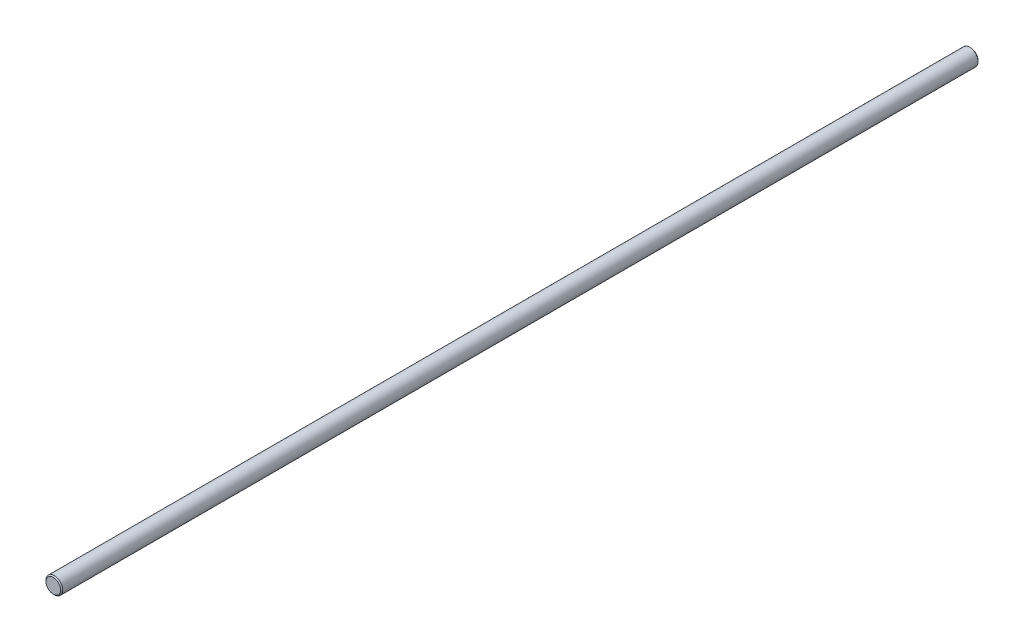
SolidWorks part; units mm, degrees
ref_plane "Front Plane" through (0, 0, 0) normal (0, 0, 1) x (1, 0, 0)
ref_plane "Top Plane" through (0, 0, 0) normal (0, 1, 0) x (1, 0, 0)
ref_plane "Right Plane" through (0, 0, 0) normal (1, 0, 0) x (0, 0, -1)
ref_plane "Plane1" through (0, 0, 0) normal (0, -1, 0) x (1, 0, 0)
sketch "Sketch1" plane through (0, 0, 0) normal (0, -1, 0) x (1, 0, 0)
  line L0 (3.5, 440) -> (0, 440)
  line L1 (0, 440) -> (0, 0)
  line L2 (0, 0) -> (3.5, 0)
  line L3 (3.5, 0) -> (4, 0.5)
  line L4 (4, 0.5) -> (4, 439.5)
  line L5 (4, 439.5) -> (3.5, 440)
  line L6 (0, 440) -> (0, 0) construction
revolve "Revolve1" add sketch "Sketch1" angle 360 about L6
